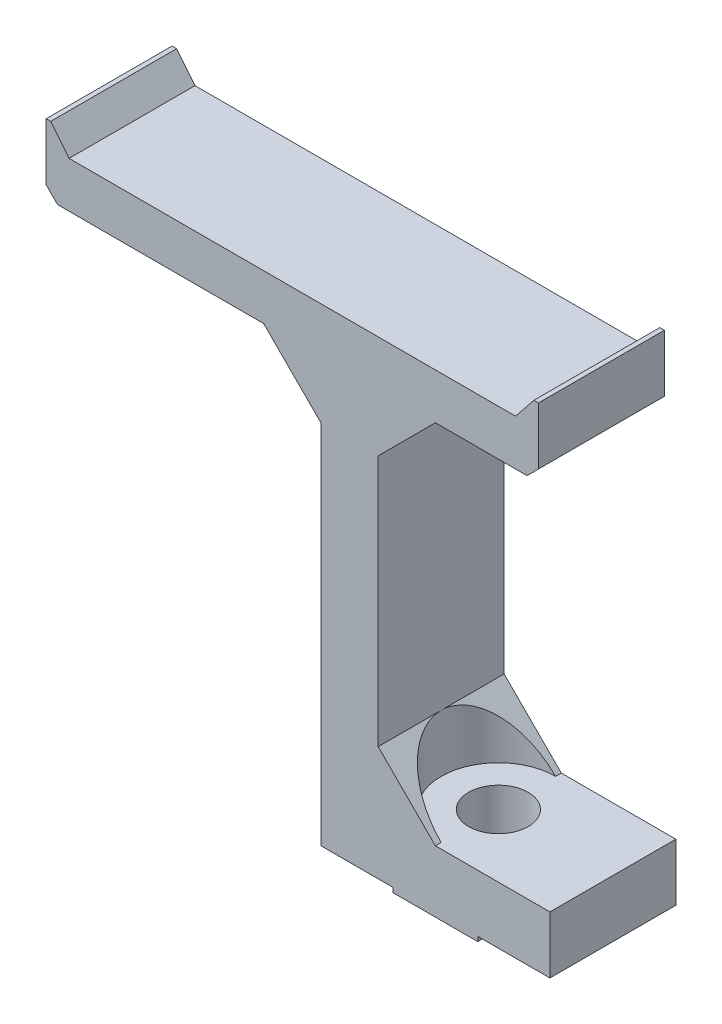
SolidWorks part; units mm, degrees
ref_plane "Спереди" through (0, 0, 0) normal (0, 0, 1) x (1, 0, 0)
ref_plane "Сверху" through (0, 0, 0) normal (0, 1, 0) x (1, 0, 0)
ref_plane "Справа" through (0, 0, 0) normal (1, 0, 0) x (0, 0, -1)
sketch "Эскиз1" plane through (0, 0, 0) normal (0, 0, 1) x (1, 0, 0)
  line L0 (-10, 0.4) -> (-3.7, 0.4)
  line L10 (-3.7, 0.4) -> (-3.7, 0)
  line L11 (-3.7, 0) -> (3.7, 0)
  line L12 (3.7, 0) -> (3.7, 0.4)
  line L13 (0, 0) -> (0, 23.4909) construction
  line L14 (3.7, 0.4) -> (10, 0.4)
  line L18 (9, 37.4) -> (-5, 37.4)
  line L19 (-34, 37.4) -> (-34, 43.4)
  line L23 (10, -29.6758) -> (10, -50029.6758) construction
  line L24 (-10, -23.6196) -> (-10, -50023.6196) construction
  line L25 (10, 0.4) -> (10, 5.4)
  line L27 (-10, 0.4) -> (-10, 37.4)
  line L32 (0, 25.4) -> (-10, 25.4) construction
  line L34 (7, 41.4) -> (-32, 41.4)
  line L36 (9, 43.4) -> (8.6, 43.4)
  line L37 (8.6, 43.4) -> (7, 41.4)
  line L38 (-34, 43.4) -> (-33.6, 43.4)
  line L39 (-33.6, 43.4) -> (-32, 41.4)
  line L40 (7, 41.4) -> (7, 37.4) construction
  line L41 (-32, 41.4) -> (-32, 37.4) construction
  line L42 (10, 5.4) -> (-5, 5.4)
  line L43 (-5, 5.4) -> (-5, 37.4)
  line L44 (9, 37.4) -> (9, 43.4)
  line L45 (-10, 37.4) -> (-34, 37.4)
  point P21 (0, 0)
  dimension "D3" = 5
  dimension "D4" = 10
  dimension "D5" = 37
  dimension "D6" = 0
  dimension "D7" = 0.4
  dimension "D8" = 0.4
  dimension "D9" = 7.4
  dimension "D10" = 0.4
  dimension "D11" = 10
  dimension "D12" = 5
  dimension "D13" = 10
  dimension "D14" = 20
  dimension "D15" = 3
  dimension "D20" = 25
  dimension "D21" = 2
  dimension "D22" = 6
  dimension "D23" = 39
  dimension "D24" = 2
  dimension "D25" = 4
  dimension "D26" = 2
  dimension "D27" = 90
extrude "Бобышка-Вытянуть1" add sketch "Эскиз1" along normal blind 11
ref_plane "Плоскость1" through (0, 41.4, 0) normal (0, -1, 0) x (-1, 0, 0)
chamfer "Фаска2" distance 5 3 edges at (-10, 37.4, 5.5) (-5, 37.4, 5.5) (-5, 5.4, 5.5)
chamfer "Фаска3" distance 1 angle 45 2 edges at (-34, 37.4, 5.5) (9, 37.4, 5.5)
sketch "Эскиз2" plane through (0, 5.4, 0) normal (0, 1, 0) x (1, 0, 0)
  line L2 (0, 0) -> (0, -11) construction
  circle A0 centre (0, -5.5) radius 2.6
  point P7 (0, -5.5)
  dimension "D1" = 5.2
extrude "Вырез-Вытянуть1" cut sketch "Эскиз2" against normal through all
sketch "Эскиз3" plane through (0, 5.4, 0) normal (0, 1, 0) x (1, 0, 0)
  circle A0 centre (0, -5.5) radius 5
  dimension "D1" = 10
extrude "Вырез-Вытянуть2" cut sketch "Эскиз3" along normal blind 5
